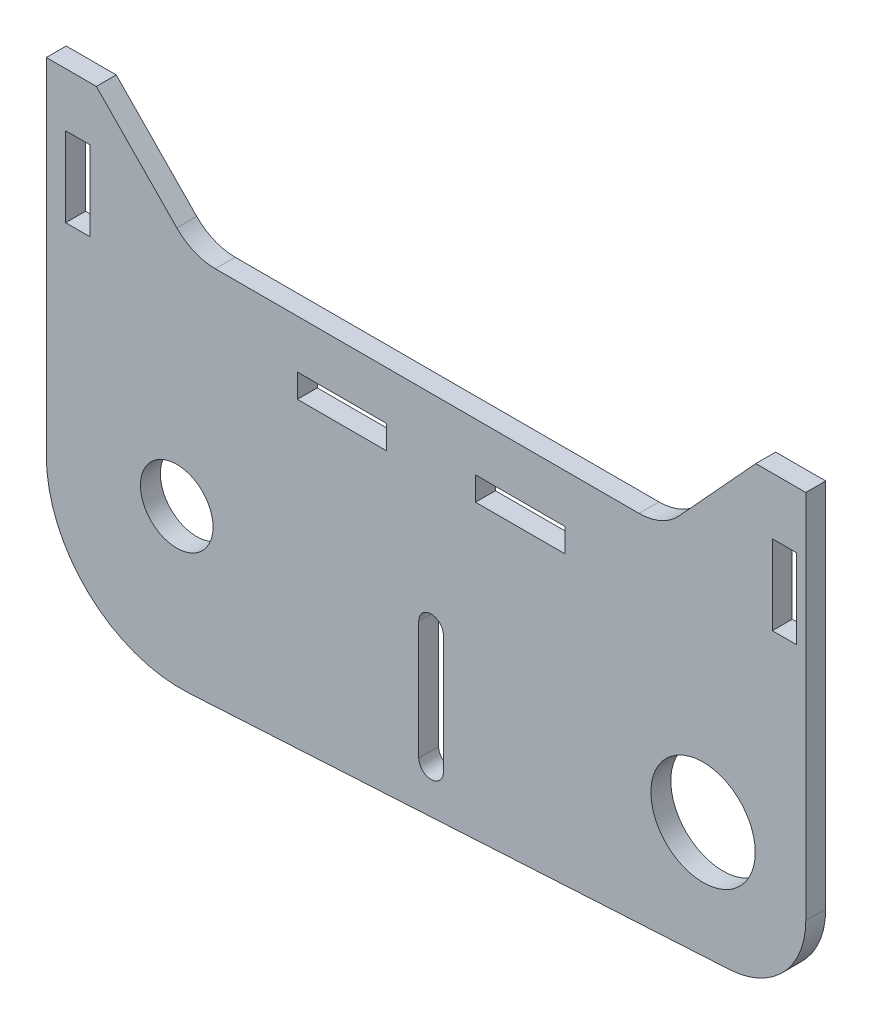
SolidWorks part; units mm, degrees
ref_plane "Front Plane" through (0, 0, 0) normal (0, 0, 1) x (1, 0, 0)
ref_plane "Top Plane" through (0, 0, 0) normal (0, 1, 0) x (1, 0, 0)
ref_plane "Right Plane" through (0, 0, 0) normal (1, 0, 0) x (0, 0, -1)
sketch "Sketch2" plane through (0, 0, 0) normal (0, 0, 1) x (1, 0, 0)
  line L0 (-66.4084, -37.4733) -> (-66.4084, 53.1267)
  line L2 (74.7905, 53.6991) -> (74.7905, -29.4009)
  line L3 (-66.4084, -37.4733) -> (74.7905, -29.4009)
  line L4 (-66.4084, 53.1267) -> (-57.1084, 53.1267)
  line L5 (-57.1084, 53.1267) -> (-39.2067, 34.8267)
  line L6 (-39.2067, 34.8267) -> (48.1933, 34.8267)
  line L7 (48.1933, 34.8267) -> (65.4905, 53.6991)
  line L8 (65.4905, 53.6991) -> (74.7905, 53.6991)
  line L9 (5.1285, 51.2939) -> (5.1285, -54.8027) construction
  line L10 (-62.8084, 28.3267) -> (-58.3084, 28.3267)
  line L11 (-62.8084, 28.3267) -> (-62.8084, 43.1267)
  line L12 (-62.8084, 43.1267) -> (-58.3084, 43.1267)
  line L13 (-58.3084, 28.3267) -> (-58.3084, 43.1267)
  line L14 (-62.8084, 28.3267) -> (-58.3084, 43.1267) construction
  line L15 (-62.8084, 43.1267) -> (-58.3084, 28.3267) construction
  line L16 (73.0654, 43.1267) -> (68.5654, 43.1267)
  line L17 (68.5654, 28.3267) -> (68.5654, 43.1267)
  line L18 (73.0654, 28.3267) -> (68.5654, 28.3267)
  line L19 (73.0654, 28.3267) -> (73.0654, 43.1267)
  line L20 (-19.7334, 25.8267) -> (-3.1334, 25.8267)
  line L21 (29.9905, 21.4267) -> (13.3905, 21.4267)
  line L22 (29.9905, 21.4267) -> (29.9905, 25.8267)
  line L23 (29.9905, 25.8267) -> (13.3905, 25.8267)
  line L24 (13.3905, 21.4267) -> (13.3905, 25.8267)
  line L25 (29.9905, 21.4267) -> (13.3905, 25.8267) construction
  line L26 (29.9905, 25.8267) -> (13.3905, 21.4267) construction
  line L27 (-3.1334, 21.4267) -> (-3.1334, 25.8267)
  line L28 (-19.7334, 21.4267) -> (-3.1334, 21.4267)
  line L29 (-19.7334, 21.4267) -> (-19.7334, 25.8267)
  line L30 (5.1285, -3.0019) -> (5.1285, -25.0371) construction
  line L31 (7.4285, -3.0019) -> (7.4285, -25.0371)
  line L32 (2.8285, -3.0019) -> (2.8285, -25.0371)
  arc A0 (7.4285, -3.0019) -> (2.8285, -3.0019) centre (5.1285, -3.0019) ccw
  arc A1 (2.8285, -25.0371) -> (7.4285, -25.0371) centre (5.1285, -25.0371) ccw
  circle A2 centre (55.6905, -8.9577) radius 9.7
  circle A3 centre (-42.1584, -6.9895) radius 6.75
  point P3 (-66.4084, 7.8267)
  point P5 (-60.5584, 35.7267)
  point P20 (21.6905, 23.6267)
  point P31 (5.1285, -14.0195)
  point P36 (5.1285, -27.3371)
  point P37 (4.191, -33.4371)
  point P42 (0, 0)
  point P43 (0, 0)
  point P45 (-37.0491, -30.9057)
  dimension "D18" = 19.4
  dimension "D21" = 13.5
  dimension "D22" = 24.25
  dimension "D1" = 90.6
  dimension "D2" = 83.1
  dimension "D3" = 141.2
  dimension "D4" = 9.3
  dimension "D5" = 87.4
  dimension "D6" = 25.6
  dimension "D7" = 18.3
  dimension "D8" = 14.8
  dimension "D9" = 4.5
  dimension "D10" = 10
  dimension "D11" = 3.6
  dimension "D12" = 16.6
  dimension "D13" = 4.4
  dimension "D14" = 44.8
  dimension "D15" = 9
  dimension "D16" = 6.1
  dimension "D17" = 4.6
  dimension "D19" = 19.1
  dimension "D20" = 21.5
  dimension "D23" = 29.05
extrude "Boss-Extrude1" add sketch "Sketch2" along normal blind 3.7
fillet "Fillet1" radius 15 1 edges at (74.7905, -29.4009, 1.85)
fillet "Fillet2" radius 25 1 edges at (-66.4084, -37.4733, 1.85)
fillet "Fillet3" radius 10 2 edges at (48.1933, 34.8267, 1.85) (-39.2067, 34.8267, 1.85)
